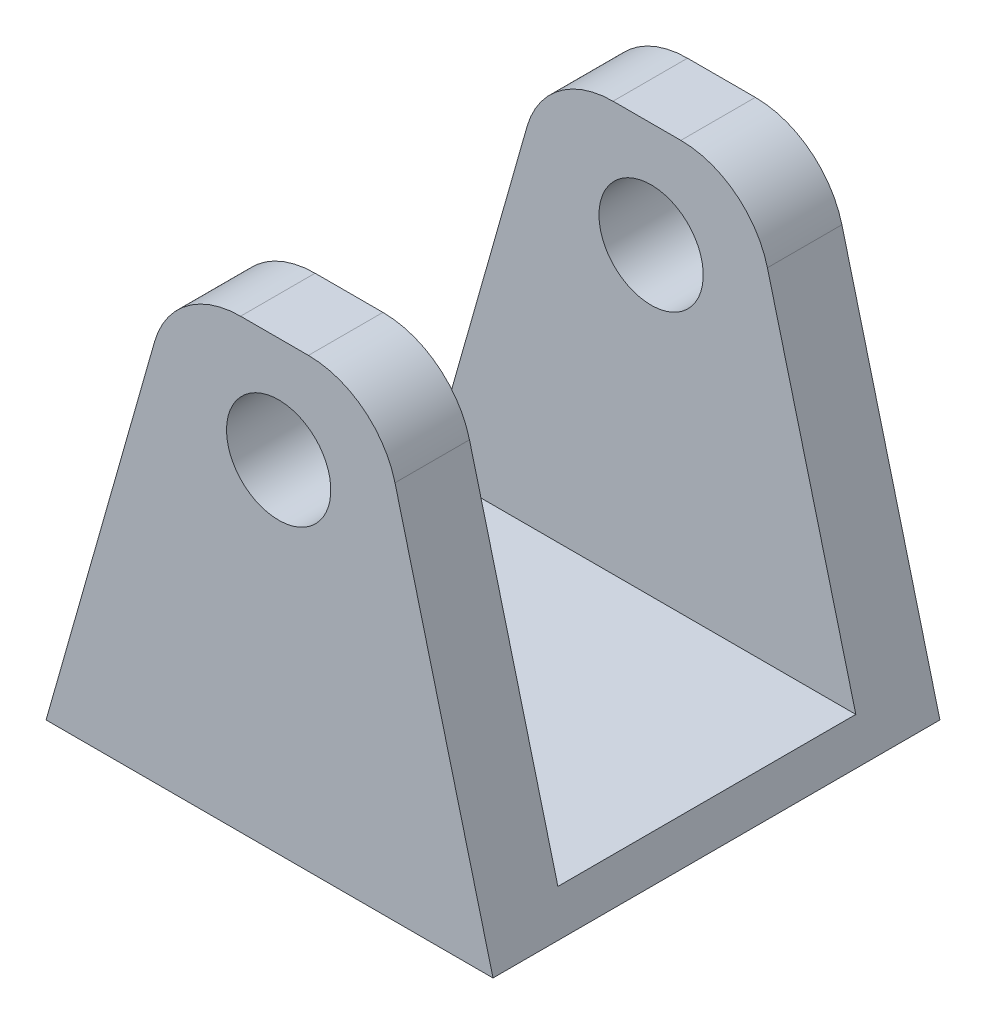
SolidWorks part; units mm, degrees
ref_plane "Alzado" through (0, 0, 0) normal (0, 0, 1) x (1, 0, 0)
ref_plane "Planta" through (0, 0, 0) normal (0, 1, 0) x (1, 0, 0)
ref_plane "Vista lateral" through (0, 0, 0) normal (1, 0, 0) x (0, 0, -1)
sketch "Croquis1" plane through (0, 0, 0) normal (0, 0, 1) x (1, 0, 0)
  line L0 (-50, -6.6786) -> (-35.4306, 44.601)
  line L1 (10, -6.6786) -> (-50, -6.6786)
  line L3 (-14.778, 53.3214) -> (-23.8875, 53.3214)
  line L7 (10, -6.6786) -> (-3.1585, 44.3195)
  arc A0 (-14.778, 53.3214) -> (-3.1585, 44.3195) centre (-14.778, 41.3214) cw
  arc A1 (-23.8875, 53.3214) -> (-35.4306, 44.601) centre (-23.8875, 41.3214) ccw
  circle A2 centre (-18.7764, 39.1607) radius 7
  point P0 (0, 0)
  point P1 (-18.7764, 39.1607)
  point P14 (-19.2479, 11.7655)
  point P15 (-18.613, 35.9497)
  dimension "D1" = 12
  dimension "D3" = 60
  dimension "D2" = 60
extrude "Saliente-Extruir1" add sketch "Croquis1" along normal blind 60
sketch "Croquis2" plane through (0, 0, 0) normal (1, 0, 0) x (0, 0, -1)
  line L0 (-60, 53.3214) -> (0, 53.3214) construction
  line L1 (-50, 108.3214) -> (-10, 108.3214)
  line L2 (-50, 108.3214) -> (-50, -1.6786)
  line L3 (-50, -1.6786) -> (-10, -1.6786)
  line L4 (-10, 108.3214) -> (-10, -1.6786)
  line L5 (-50, 108.3214) -> (-10, -1.6786) construction
  line L6 (-50, -1.6786) -> (-10, 108.3214) construction
  point P0 (-30, 53.3214)
  dimension "D1" = 110
  dimension "D2" = 40
extrude "Cortar-Extruir1" cut sketch "Croquis2" against normal through all both and the other way through all
sketch "Croquis3" plane through (0, -6.6786, 0) normal (0, -1, 0) x (1, 0, 0)
  circle A0 centre (-19.61, 29.155) radius 7
  point P2 (-19.61, 29.155)
extrude "Saliente-Extruir2" add sketch "Croquis3" along normal blind 20
